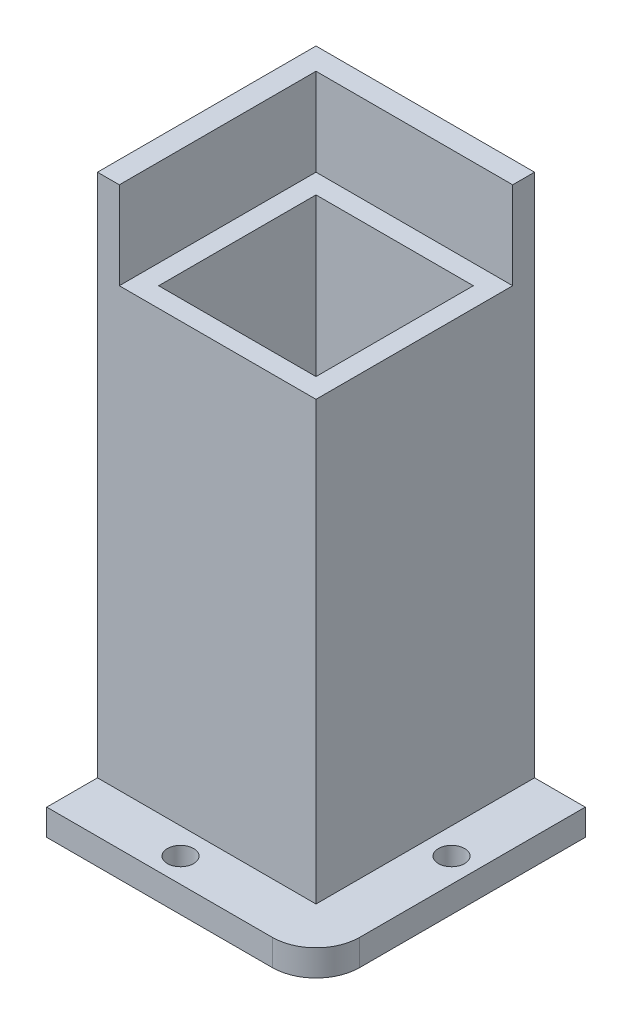
SolidWorks part; units mm, degrees
ref_plane "Front Plane" through (0, 0, 0) normal (0, 0, 1) x (1, 0, 0)
ref_plane "Top Plane" through (0, 0, 0) normal (0, 1, 0) x (1, 0, 0)
ref_plane "Right Plane" through (0, 0, 0) normal (1, 0, 0) x (0, 0, -1)
sketch "Sketch1" plane through (0, 0, 0) normal (0, 1, 0) x (1, 0, 0)
  line L1 (-12.5, 12.5) -> (12.5, 12.5)
  line L2 (-12.5, 12.5) -> (-12.5, -12.5)
  line L3 (-12.5, -12.5) -> (12.5, -12.5)
  line L4 (12.5, 12.5) -> (12.5, -12.5)
  line L5 (-12.5, 12.5) -> (12.5, -12.5) construction
  line L6 (-12.5, -12.5) -> (12.5, 12.5) construction
  point P0 (0, 0)
  dimension "D1" = 25
  dimension "D2" = 25
extrude "Boss-Extrude1" add sketch "Sketch1" along normal blind 63
sketch "Sketch2" plane through (0, 63, 0) normal (0, 1, 0) x (1, 0, 0)
  line L1 (12.5, -12.5) -> (-10, -12.5)
  line L2 (12.5, -12.5) -> (12.5, 10)
  line L3 (12.5, 10) -> (-10, 10)
  line L4 (-10, -12.5) -> (-10, 10)
  dimension "D1" = 22.5
  dimension "D2" = 22.5
extrude "Cut-Extrude2" cut sketch "Sketch2" against normal blind 10
sketch "Sketch4" plane through (0, 0, 0) normal (0, -1, 0) x (1, 0, 0)
  line L1 (-12.5, -12.5) -> (18.3, -12.5)
  line L2 (-12.5, -12.5) -> (-12.5, 18.3)
  line L3 (-12.5, 18.3) -> (13.3, 18.3)
  line L4 (18.3, -12.5) -> (18.3, 13.3)
  line L5 (12.5, 12.5) -> (-12.5, 12.5)
  line L6 (12.5, 12.5) -> (12.5, -12.5)
  line L7 (12.5, -12.5) -> (-12.5, -12.5)
  line L8 (-12.5, 12.5) -> (-12.5, -12.5)
  arc A0 (13.3, 18.3) -> (18.3, 13.3) centre (13.3, 13.3) cw
  circle A1 centre (0, 15.5) radius 1.5
  circle A2 centre (15.5, 0) radius 1.5
  point P11 (18.3, 18.3)
  line M9 (12.5, -12.5) -> (12.5, 12.5)
  line M10 (12.5, 12.5) -> (-12.5, 12.5)
  dimension "D3" = 5
  dimension "D4" = 3
  dimension "D5" = 3
  dimension "D1" = 30.8
  dimension "D2" = 30.8
  dimension "D6" = 12.5
  dimension "D7" = 12.5
  dimension "D8" = 28
  dimension "D9" = 28
extrude "Boss-Extrude2" add sketch "Sketch4" against normal blind 3 contours L1 L4 L3 L2 M10 M9
sketch "Sketch5" plane through (0, 53, 0) normal (0, 1, 0) x (1, 0, 0)
  line L0 (-10, -1.25) -> (12.5, -1.25) construction
  line L1 (-10, 10) -> (-10, -12.5) construction
  line L2 (12.5, -12.5) -> (12.5, 10) construction
  line L4 (-7.75, 7.75) -> (10.25, 7.75)
  line L5 (-7.75, 7.75) -> (-7.75, -10.25)
  line L6 (-7.75, -10.25) -> (10.25, -10.25)
  line L7 (10.25, 7.75) -> (10.25, -10.25)
  line L8 (-7.75, 7.75) -> (10.25, -10.25) construction
  line L9 (-7.75, -10.25) -> (10.25, 7.75) construction
  point P6 (1.25, -1.25)
  dimension "D1" = 18
  dimension "D2" = 18
extrude "Cut-Extrude3" cut sketch "Sketch5" against normal blind 50
